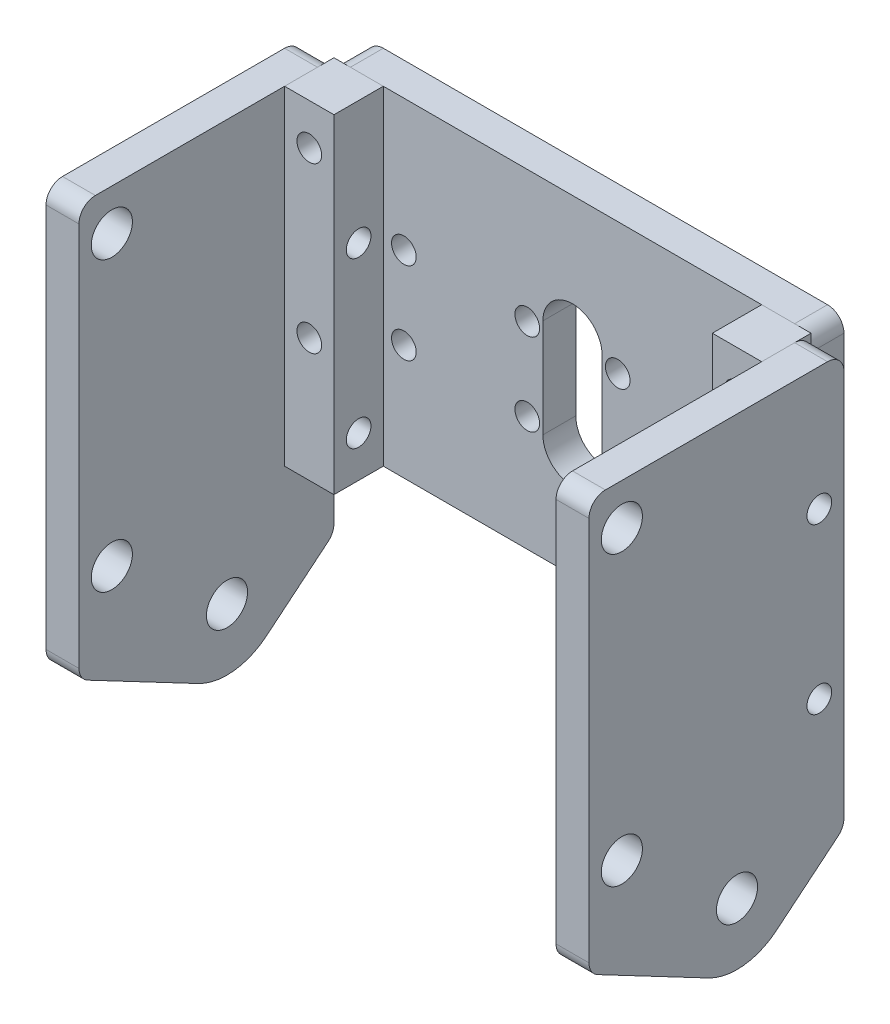
SolidWorks part; units mm, degrees
ref_plane "前视基准面" through (0, 0, 0) normal (0, 0, 1) x (1, 0, 0)
ref_plane "上视基准面" through (0, 0, 0) normal (0, 1, 0) x (1, 0, 0)
ref_plane "右视基准面" through (0, 0, 0) normal (1, 0, 0) x (0, 0, -1)
other "Configuration Table"
sketch "草图1" plane through (0, 0, 0) normal (0, 0, 1) x (1, 0, 0)
  line L0 (0, 0) -> (0, -1) construction
  line L1 (0, -1) -> (-13, -1) construction
  line L7 (-29, -20) -> (29, -20)
  line L8 (20.5, 4) -> (5.5, -6) construction
  line L9 (-20.5, -6) -> (-5.5, -6) construction
  line L10 (-20.5, -6) -> (-20.5, 4) construction
  line L11 (-20.5, 4) -> (-5.5, 4) construction
  line L12 (-5.5, -6) -> (-5.5, 4) construction
  line L13 (-20.5, -6) -> (-5.5, 4) construction
  line L14 (-20.5, 4) -> (-5.5, -6) construction
  line L15 (20.5, -6) -> (5.5, 4) construction
  line L16 (5.5, -6) -> (5.5, 4) construction
  line L17 (20.5, 4) -> (5.5, 4) construction
  line L18 (20.5, -6) -> (20.5, 4) construction
  line L19 (20.5, -6) -> (5.5, -6) construction
  line L20 (-29, -20) -> (-29, 20)
  line L21 (-29, 20) -> (29, 20)
  line L22 (29, -20) -> (29, 20)
  line L23 (-29, -20) -> (29, 20) construction
  line L24 (-29, 20) -> (29, -20) construction
  circle A0 centre (-5.5, 4) radius 1.5
  circle A1 centre (-5.5, -6) radius 1.5
  circle A2 centre (-20.5, -6) radius 1.5
  circle A3 centre (-20.5, 4) radius 1.5
  circle A4 centre (20.5, 4) radius 1.5
  circle A5 centre (20.5, -6) radius 1.5
  circle A6 centre (5.5, -6) radius 1.5
  circle A7 centre (5.5, 4) radius 1.5
  dimension "D3" = 3
  dimension "D1" = 15
  dimension "D2" = 10
  dimension "D4" = 13
  dimension "D5" = 40
  dimension "D6" = 58
  dimension "D7" = 1
extrude "凸台-拉伸1" add sketch "草图1" along normal blind 4
sketch "草图2" plane through (0, 0, 4) normal (0, 0, 1) x (1, 0, 0)
  line L0 (0, 0) -> (0, 5) construction
  line L1 (29, -20) -> (29, 20) construction
  line L2 (-26, -5) -> (26, -5) construction
  line L3 (-26, -5) -> (-26, 15) construction
  line L4 (-26, 15) -> (26, 15) construction
  line L5 (26, -5) -> (26, 15) construction
  line L6 (-26, -5) -> (26, 15) construction
  line L7 (-26, 15) -> (26, -5) construction
  line L8 (29, 20) -> (-29, 20) construction
  circle A0 centre (26, -5) radius 1.5
  circle A1 centre (26, 15) radius 1.5
  circle A2 centre (-26, 15) radius 1.5
  circle A3 centre (-26, -5) radius 1.5
  dimension "D2" = 3
  dimension "D1" = 3
  dimension "D3" = 20
  dimension "D4" = 5
extrude "切除-拉伸1" cut sketch "草图2" against normal up to surface (4 mm away) up to face at (4, -6, 0)
sketch "草图3" plane through (0, 0, 4) normal (0, 0, 1) x (1, 0, 0)
  line L0 (-29, -20) -> (29, -20) construction
  line L1 (-29, 20) -> (-23, 20)
  line L2 (-29, 20) -> (-29, -20)
  line L3 (-29, -20) -> (-23, -20)
  line L4 (-23, 20) -> (-23, -20)
  line L5 (0, 0) -> (0, 28.7249) construction
  line L6 (23, 20) -> (23, -20)
  line L7 (29, -20) -> (23, -20)
  line L8 (29, 20) -> (29, -20)
  line L9 (29, 20) -> (23, 20)
  circle A0 centre (-26, 15) radius 1.5 construction
  circle A1 centre (-26, -5) radius 1.5 construction
  circle A2 centre (-26, -5) radius 1.5
  circle A3 centre (-26, 15) radius 1.5
  circle A4 centre (26, 15) radius 1.5
  circle A5 centre (26, -5) radius 1.5
  dimension "D1" = 6
extrude "凸台-拉伸2" add sketch "草图3" along normal blind 6 separate body
sketch "草图4" plane through (-29, 0, 0) normal (-1, 0, 0) x (0, 0, 1)
  line L0 (7, -20) -> (7, -15) construction
  line L1 (10, -20) -> (4, -20) construction
  line L2 (7, -15) -> (7, 5) construction
  circle A0 centre (7, -15) radius 1.5
  circle A1 centre (7, 5) radius 1.5
  dimension "D3" = 3
  dimension "D1" = 20
  dimension "D2" = 5
extrude "切除-拉伸2" cut sketch "草图4" against normal up to surface (58 mm away)
sketch "草图5" plane through (-29, 0, 0) normal (-1, 0, 0) x (0, 0, 1)
  line L1 (4, 20) -> (35, 20)
  line L2 (4, 20) -> (4, -20)
  line L3 (4, -20) -> (35, -20)
  line L4 (35, -20) -> (35, 20)
  circle A1 centre (7, 5) radius 1.5
  circle A2 centre (7, 5) radius 1.5
  circle A3 centre (7, -15) radius 1.5
  circle A4 centre (7, -15) radius 1.5
  dimension "D3" = 31
  dimension "D1" = 0
  dimension "D2" = 0
extrude "凸台-拉伸3" add sketch "草图5" along normal blind 4 separate body
sketch "草图6" plane through (-33, 0, 0) normal (-1, 0, 0) x (0, 0, 1)
  line L0 (35, -20) -> (35, 20) construction
  line L1 (4, -20) -> (35, -20)
  line L2 (4, -20) -> (4, -30)
  line L3 (4, -30) -> (35, -30)
  line L4 (35, -20) -> (35, -30)
  dimension "D1" = 10
extrude "凸台-拉伸4" add sketch "草图6" against normal blind 4
sketch "草图7" plane through (-33, 0, 0) normal (-1, 0, 0) x (0, 0, 1)
  line L0 (31, 15) -> (31, -20) construction
  line L1 (35, -30) -> (35, 20) construction
  line L3 (35, 20) -> (4, 20) construction
  circle A0 centre (31, 15) radius 2.5
  circle A1 centre (31, -20) radius 2.5
  dimension "D2" = 5
  dimension "D4" = 5
  dimension "D1" = 35
  dimension "D3" = 4
extrude "切除-拉伸3" cut sketch "草图7" against normal up to surface (4 mm away) up to face at (-29, -5, 19.5)
sketch "草图8" plane through (-33, 0, 0) normal (-1, 0, 0) x (0, 0, 1)
  line L0 (4, -30) -> (35, -30) construction
  line L1 (4, 20) -> (4, -30) construction
  line L2 (35, -30) -> (20.4937, -37.6366)
  line L3 (4, -30) -> (12.228, -36.786)
  line L4 (4, -30) -> (35, -30)
  circle A0 centre (17, -31) radius 2.5
  circle A1 centre (17, -31) radius 7.5
  line M8 (4, -30) -> (35, -30)
  dimension "D1" = 5
  dimension "D2" = 1
  dimension "D3" = 15
  dimension "D4" = 13
extrude "凸台-拉伸5" add sketch "草图8" against normal up to surface (4 mm away) contours A1 L2 L3 M8 | A1 L3 M8 | A1 L2 L4
sketch "草图9" plane through (0, 0, 0) normal (0, 0, -1) x (-1, 0, 0)
  line L0 (0, 0) -> (0, -9.2107) construction
  line L1 (0, -7) -> (0, 5) construction
  line L2 (-3.6, -7) -> (-3.6, 5)
  line L3 (3.6, -7) -> (3.6, 5)
  arc A0 (-3.6, -7) -> (3.6, -7) centre (0, -7) ccw
  arc A1 (3.6, 5) -> (-3.6, 5) centre (0, 5) ccw
  circle A2 centre (5.5, 4) radius 1.5 construction
  point P5 (0, -1)
  dimension "D1" = 3.6
  dimension "D2" = 11
  dimension "D3" = 1
extrude "切除-拉伸4" cut sketch "草图9" against normal up to surface (4 mm away) up to face at (-24.5, -5, 4)
fillet "圆角1" radius 2 4 edges at (29, -20, 2) (-29, -20, 2) (-29, 20, 2) (29, 20, 2)
fillet "圆角2" radius 2 4 edges at (-31, 20, 35) (-31, -30, 4) (-31, -30, 35) (-31, 20, 4)
sketch "草图11" plane through (-33, 0, 0) normal (-1, 0, 0) x (0, 0, 1)
  circle A0 centre (17, -31) radius 2.5
  arc A1 (14.7087, -30) -> (19.2913, -30) centre (17, -31) ccw construction
extrude "切除-拉伸5" cut sketch "草图11" against normal up to surface (4 mm away) up to face at (-29, -31.75, 17)
mirror "镜向1" about plane through (0, 0, 0) normal (1, 0, 0) of bodies 118 115
